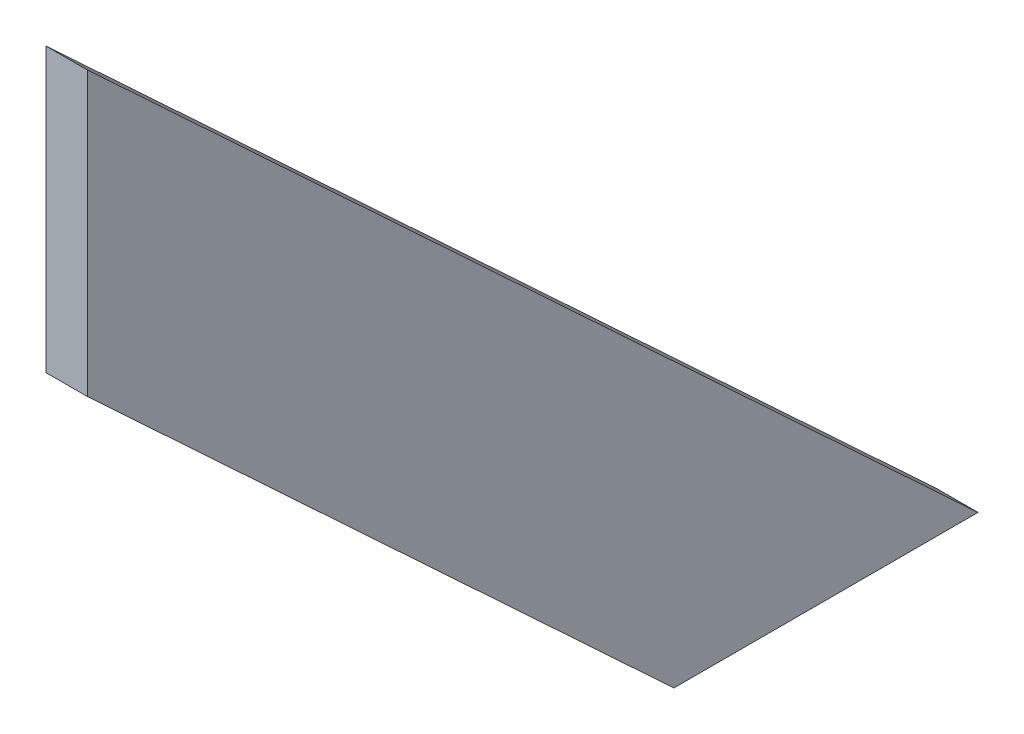
SolidWorks part; units mm, degrees
material "AISI 304"
ref_plane "Front Plane" through (0, 0, 0) normal (0, 0, 1) x (1, 0, 0)
ref_plane "Top Plane" through (0, 0, 0) normal (0, 1, 0) x (1, 0, 0)
ref_plane "Right Plane" through (0, 0, 0) normal (1, 0, 0) x (0, 0, -1)
sketch "Sketch1" plane through (0, 0, 0) normal (1, 0, 0) x (0, 0, -1)
  line L0 (28.318, 0) -> (43, 0)
  line L1 (43, 0) -> (0, 40)
  line L2 (0, 40) -> (0, 26.3423)
  line L3 (0, 26.3423) -> (28.318, 0)
  line L4 (0, 26.3423) -> (0, 0) construction
  line L5 (0, 0) -> (28.318, 0) construction
  dimension "D1" = 43
  dimension "D2" = 40
  dimension "D3" = 10
extrude "Boss-Extrude1" add sketch "Sketch1" along normal blind 2
